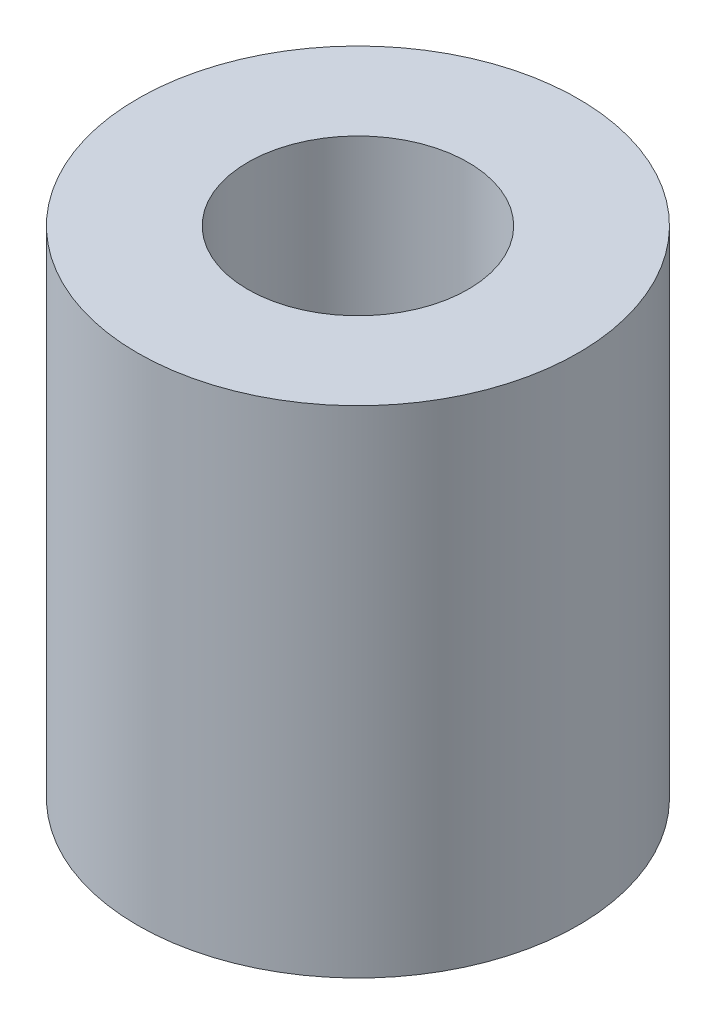
SolidWorks part; units mm, degrees
ref_plane "Front Plane" through (0, 0, 0) normal (0, 0, 1) x (1, 0, 0)
ref_plane "Top Plane" through (0, 0, 0) normal (0, 1, 0) x (1, 0, 0)
ref_plane "Right Plane" through (0, 0, 0) normal (1, 0, 0) x (0, 0, -1)
sketch "Sketch1" plane through (0, 0, 0) normal (0, 1, 0) x (1, 0, 0)
  circle A0 centre (0, 0) radius 6.35
  dimension "D1" = 12.7
extrude "Boss-Extrude1" add sketch "Sketch1" along normal blind 14.2875
sketch "Sketch2" plane through (0, 14.2875, 0) normal (0, 1, 0) x (1, 0, 0)
  circle A0 centre (0, 0) radius 3.175
  dimension "D1" = 6.35
extrude "Cut-Extrude1" cut sketch "Sketch2" against normal blind 17.4625
